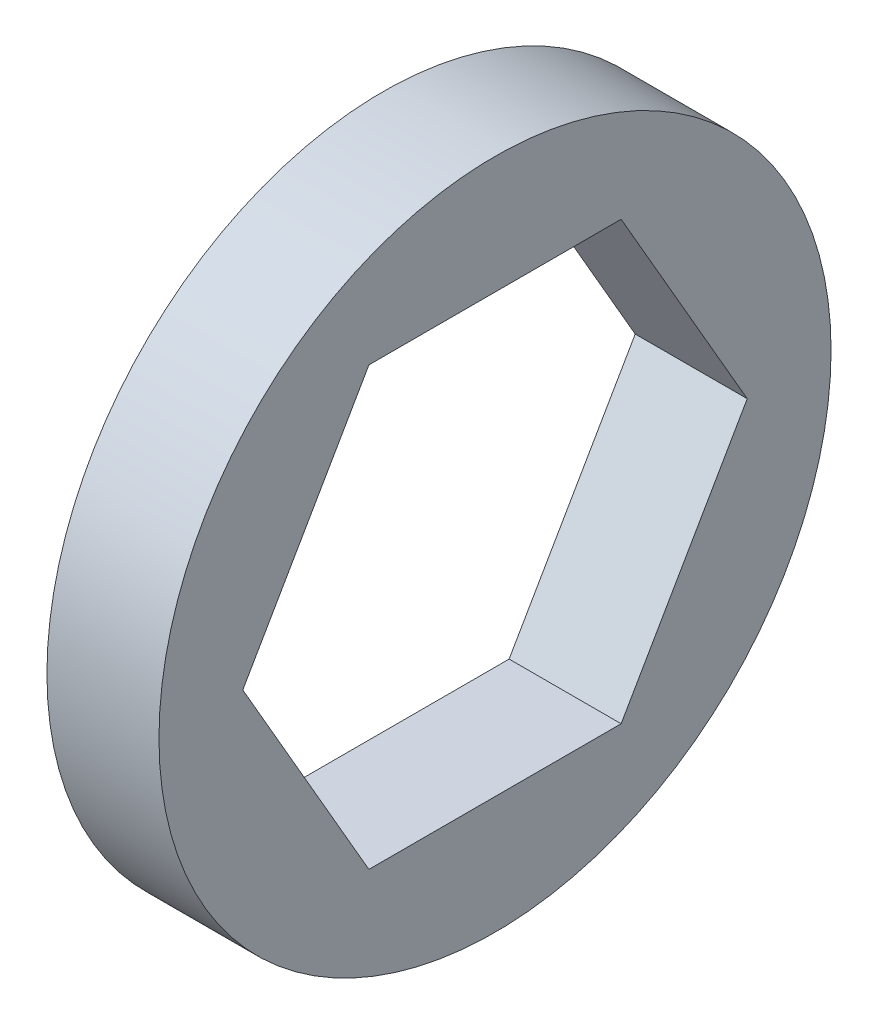
SolidWorks part; units mm, degrees
ref_plane "Front Plane" through (0, 0, 0) normal (0, 0, 1) x (1, 0, 0)
ref_plane "Top Plane" through (0, 0, 0) normal (0, 1, 0) x (1, 0, 0)
ref_plane "Right Plane" through (0, 0, 0) normal (1, 0, 0) x (0, 0, -1)
sketch "Sketch1" plane through (0, 0, 0) normal (1, 0, 0) x (0, 0, -1)
  line L1 (5.7192, 0) -> (2.8596, 4.953)
  line L2 (2.8596, 4.953) -> (-2.8596, 4.953)
  line L3 (-2.8596, 4.953) -> (-5.7192, 0)
  line L4 (-5.7192, 0) -> (-2.8596, -4.953)
  line L5 (-2.8596, -4.953) -> (2.8596, -4.953)
  line L6 (2.8596, -4.953) -> (5.7192, 0)
  circle A0 centre (0, 0) radius 4.953 construction
  circle A1 centre (0, 0) radius 7.62
  dimension "D1" = 9.906
  dimension "D2" = 15.24
extrude "Boss-Extrude1" add sketch "Sketch1" along normal blind 2.54
